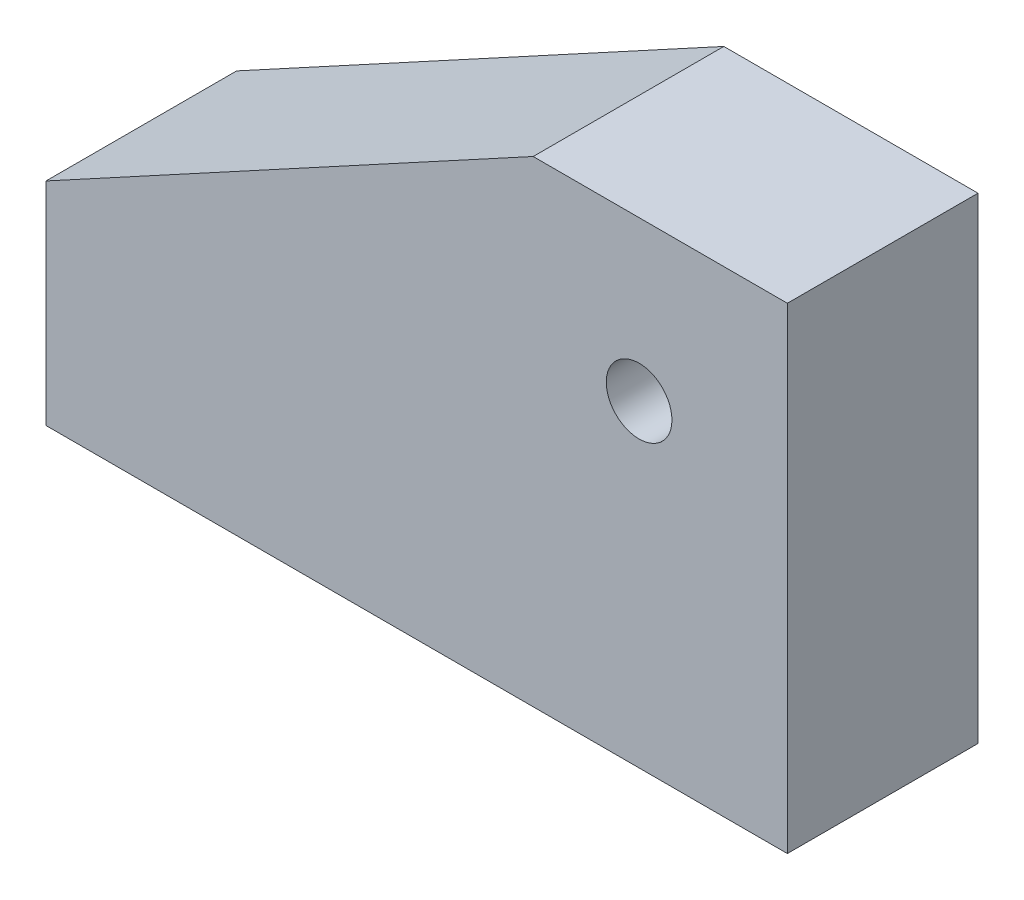
SolidWorks part; units mm, degrees
ref_plane "Front Plane" through (0, 0, 0) normal (0, 0, 1) x (1, 0, 0)
ref_plane "Top Plane" through (0, 0, 0) normal (0, 1, 0) x (1, 0, 0)
ref_plane "Right Plane" through (0, 0, 0) normal (1, 0, 0) x (0, 0, -1)
sketch "Sketch1" plane through (0, 0, 0) normal (0, 0, 1) x (1, 0, 0)
  line L0 (-35, 0) -> (35, 0)
  line L1 (35, 0) -> (35, 45)
  line L2 (35, 45) -> (11, 45)
  line L3 (11, 45) -> (-35, 20)
  line L4 (-35, 20) -> (-35, 0)
  circle A0 centre (21, 30) radius 3.1
  point P4 (0, 0)
  dimension "D5" = 6.2
  dimension "D6" = 30
  dimension "D7" = 14
  dimension "D1" = 70
  dimension "D2" = 45
  dimension "D3" = 24
  dimension "D4" = 20
extrude "Boss-Extrude1" add sketch "Sketch1" along normal mid plane 18
sketch "Sketch3" plane through (0, 0, 0) normal (0, -1, 0) x (1, 0, 0)
  line L0 (-35, -9) -> (35, -9) construction
  line L1 (35, 9) -> (35, -9) construction
  circle A0 centre (19, -5.5) radius 2
  circle A1 centre (-13, -5.5) radius 2
  point P4 (0, 0)
  dimension "D1" = 3.5
  dimension "D2" = 4
  dimension "D3" = 16
  dimension "D4" = 32
extrude "Cut-Extrude1" cut sketch "Sketch3" against normal blind 10
